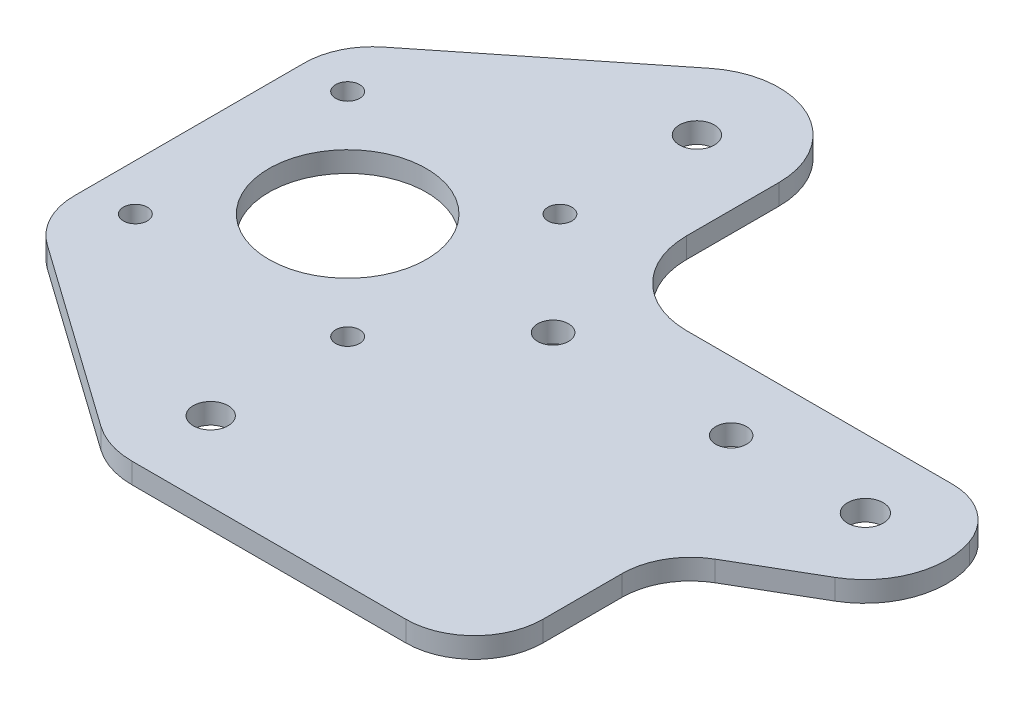
SolidWorks part; units mm, degrees
material "AISI 1020"
ref_plane "Front Plane" through (0, 0, 0) normal (0, 0, 1) x (1, 0, 0)
ref_plane "Top Plane" through (0, 0, 0) normal (0, 1, 0) x (1, 0, 0)
ref_plane "Right Plane" through (0, 0, 0) normal (1, 0, 0) x (0, 0, -1)
sketch "Sketch2" plane through (0, 0, 0) normal (0, 1, 0) x (1, 0, 0)
  line L0 (0, -16.785) -> (0, 16.785)
  line L1 (3.7653, 24.6035) -> (30.2855, 45.7516)
  line L2 (4.2186, -24.9444) -> (31.12, -44.0057)
  line L4 (49.7672, 36.3694) -> (49.7672, 22.8694)
  line L5 (37.7687, -46.1224) -> (77.7687, -46.1224)
  line L6 (61.7672, 10.8694) -> (100.5972, 10.8694)
  line L7 (87.7687, -36.1224) -> (87.7687, -24.5724)
  line L8 (92.7385, -15.9296) -> (103.8012, -9.491)
  arc A0 (0, 16.785) -> (3.7653, 24.6035) centre (10, 16.785) cw
  arc A1 (0, -16.785) -> (4.2186, -24.9444) centre (10, -16.785) ccw
  arc A2 (31.12, -44.0057) -> (37.7687, -46.1224) centre (37.7687, -34.6224) ccw
  arc A3 (30.2855, 45.7516) -> (49.7672, 36.3694) centre (37.7672, 36.3694) cw
  arc A4 (49.7672, 22.8694) -> (61.7672, 10.8694) centre (61.7672, 22.8694) ccw
  arc A5 (77.7687, -46.1224) -> (87.7687, -36.1224) centre (77.7687, -36.1224) ccw
  arc A6 (87.7687, -24.5724) -> (92.7385, -15.9296) centre (97.7687, -24.5724) cw
  arc A7 (100.5972, 10.8694) -> (109.094, 4.8367) centre (100.5972, 1.8694) cw
  arc A8 (109.094, 4.8367) -> (103.8012, -9.491) centre (97.7649, 0.8803) cw
  circle A9 centre (37.7672, 36.3694) radius 2.55
  circle A10 centre (37.7672, 16.3694) radius 1.75
  circle A11 centre (22.26, 0.8776) radius 11.5
  circle A12 centre (37.7672, -14.6306) radius 1.75
  circle A13 centre (6.7672, -14.6306) radius 1.75
  circle A14 centre (6.7672, 16.3694) radius 1.75
  circle A15 centre (52.26, 0.8776) radius 2.25
  circle A16 centre (78.26, 0.8776) radius 2.25
  circle A17 centre (97.86, 0.8776) radius 2.6
  circle A18 centre (37.7672, -34.6306) radius 2.55
  point P42 (22.2672, 0.8694)
  dimension "D2" = 10
  dimension "D3" = 10
  dimension "D8" = 12
  dimension "D10" = 11.5
  dimension "D12" = 12
  dimension "D14" = 10
  dimension "D17" = 10
  dimension "D20" = 9
  dimension "D21" = 12
  dimension "D7" = 5.1
  dimension "D22" = 23
  dimension "D23" = 3.5
  dimension "D24" = 22.26
  dimension "D25" = 47
  dimension "D26" = 20
  dimension "D28" = 31
  dimension "D29" = 30
  dimension "D30" = 4.5
  dimension "D31" = 26
  dimension "D32" = 4.5
  dimension "D33" = 5.2
  dimension "D34" = 19.6
  dimension "D35" = 5.1
  dimension "D36" = 20
  dimension "D1" = 33.57
  dimension "D4" = 33.92
  dimension "D5" = 32.97
  dimension "D6" = 38.57
  dimension "D9" = 13.5
  dimension "D11" = 40
  dimension "D13" = 38.83
  dimension "D15" = 11.55
  dimension "D16" = 90
  dimension "D18" = 12.8
  dimension "D19" = 30.2
  dimension "D27" = 4
extrude "Boss-Extrude1" add sketch "Sketch2" along normal blind 3
